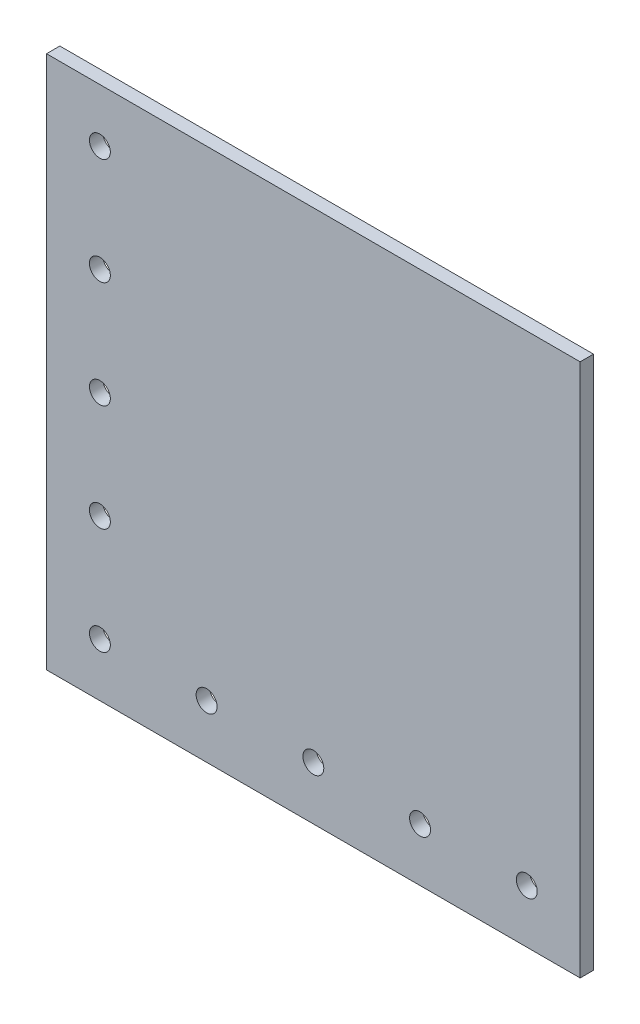
SolidWorks part; units mm, degrees
ref_plane "Front Plane" through (0, 0, 0) normal (0, 0, 1) x (1, 0, 0)
ref_plane "Top Plane" through (0, 0, 0) normal (0, 1, 0) x (1, 0, 0)
ref_plane "Right Plane" through (0, 0, 0) normal (1, 0, 0) x (0, 0, -1)
sketch "Sketch1" plane through (0, 0, 0) normal (0, 0, 1) x (1, 0, 0)
  line L0 (0, 127) -> (0, 0)
  line L1 (0, 0) -> (127, 0)
  line L2 (127, 0) -> (127, 25.4)
  line L5 (0, 127) -> (127, 127)
  line L6 (127, 127) -> (127, 25.4)
  circle A0 centre (114.3, 12.7) radius 2.4892
  circle A1 centre (88.9, 12.7) radius 2.4892
  circle A2 centre (63.5, 12.7) radius 2.4892
  circle A3 centre (38.1, 12.7) radius 2.4892
  circle A4 centre (12.7, 12.7) radius 2.4892
  circle A5 centre (12.7, 38.1) radius 2.4892
  circle A6 centre (12.7, 63.5) radius 2.4892
  circle A7 centre (12.7, 88.9) radius 2.4892
  circle A8 centre (12.7, 114.3) radius 2.4892
  point P9 (127, 12.7)
  dimension "D5" = 4.9784
  dimension "D6" = 12.7
  dimension "D8" = 25.4
  dimension "D10" = 25.4
  dimension "D1" = 25.4
  dimension "D3" = 127
  dimension "D4" = 127
  dimension "D7" = 5
  dimension "D9" = 5
extrude "Boss-Extrude1" add sketch "Sketch1" along normal mid plane 3.175
